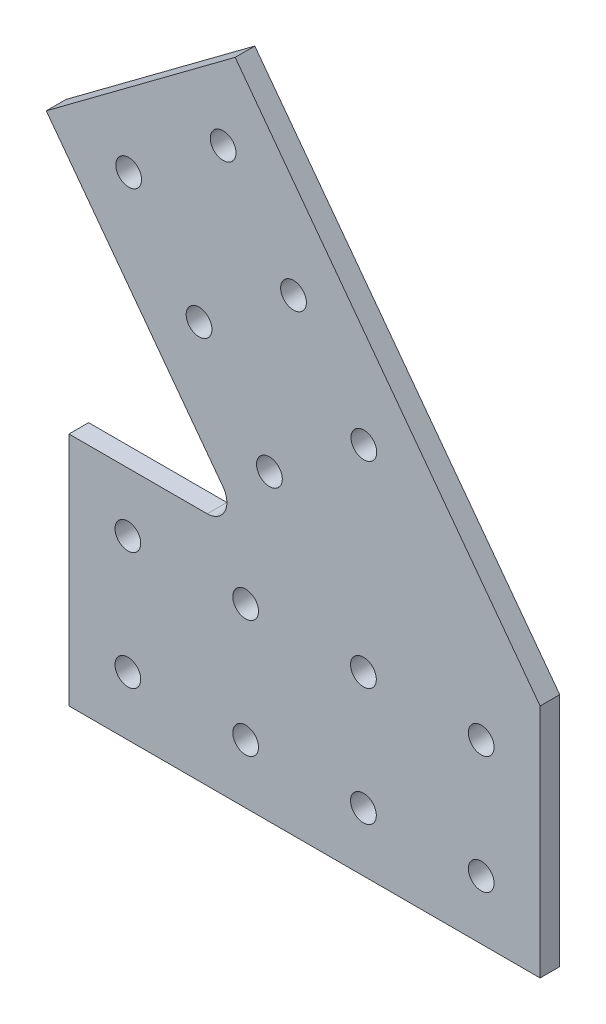
SolidWorks part; units mm, degrees
material "6061-T6 (SS)"
ref_plane "Front" through (0, 0, 0) normal (0, 0, 1) x (1, 0, 0)
ref_plane "Top" through (0, 0, 0) normal (0, 1, 0) x (1, 0, 0)
ref_plane "Right" through (0, 0, 0) normal (1, 0, 0) x (0, 0, -1)
sketch "Sketch2" plane through (0, 0, 0) normal (0, 0, 1) x (1, 0, 0)
  line L0 (0, 0) -> (152.4, 0)
  line L1 (152.4, 0) -> (152.4, 76.2)
  line L2 (152.4, 76.2) -> (53.7552, 208.5904)
  line L3 (53.7552, 208.5904) -> (-7.3481, 163.062)
  line L4 (-7.3481, 163.062) -> (57.3733, 76.2)
  line L5 (57.3733, 76.2) -> (0, 76.2)
  line L6 (0, 76.2) -> (0, 0)
  dimension "D1" = 152.4
  dimension "D2" = 76.2
  dimension "D3" = 76.2
  dimension "D4" = 76.2
  dimension "D5" = 53.31
  dimension "D6" = 165.1
extrude "Boss-Extrude1" add sketch "Sketch2" along normal blind 6.35
hole_wizard "21/64 (0.32813) Diameter Hole1" positions "Sketch3" profile "Sketch4" hole size "21/64" standard "ANSI Inch" end condition through all
sketch "Sketch3" plane through (0, 0, 6.35) normal (0, 0, 1) x (1, 0, 0)
  line L0 (152.4, 0) -> (152.4, 76.2) construction
  line L1 (0, 0) -> (152.4, 0) construction
  point P0 (133.35, 19.05)
  dimension "D1" = 19.05
  dimension "D2" = 19.05
sketch "Sketch4" plane through (133.35, 19.05, 6.35) normal (1, 0, 0) x (0, -1, 0)
  line L0 (0, 0) -> (0, 6.35)
  line L1 (0, 6.35) -> (4.1673, 6.35)
  line L2 (4.1673, 6.35) -> (4.1673, 0)
  line L5 (4.1673, 0) -> (0, 0)
  line L11 (0, -6.35) -> (0, 107.95) construction
  dimension "Thru Hole Dia." = 8.3345
  dimension "Thru Hole Depth" = 6.35
pattern_linear "LPattern1" count 4 spacing 38.1 along (-1, 0, 0) count 2 spacing 38.1 along (0, 1, 0) of "21/64 (0.32813) Diameter Hole1"
hole_wizard "21/64 (0.32813) Diameter Hole2" positions "Sketch5" profile "Sketch6" hole size "21/64" standard "ANSI Inch" end condition through all
sketch "Sketch5" plane through (0, 0, 6.35) normal (0, 0, 1) x (1, 0, 0)
  line L0 (152.4, 76.2) -> (53.7552, 208.5904) construction
  line L1 (53.7552, 208.5904) -> (-7.3481, 163.062) construction
  point P0 (49.8615, 181.9325)
  dimension "D1" = 19.05
  dimension "D2" = 19.05
sketch "Sketch6" plane through (49.8615, 181.9325, 6.35) normal (1, 0, 0) x (0, -1, 0)
  line L0 (0, 0) -> (0, 6.35)
  line L1 (0, 6.35) -> (4.1673, 6.35)
  line L2 (4.1673, 6.35) -> (4.1673, 0)
  line L5 (4.1673, 0) -> (0, 0)
  line L11 (0, -6.35) -> (0, 107.95) construction
  dimension "Thru Hole Dia." = 8.3345
  dimension "Thru Hole Depth" = 6.35
pattern_linear "LPattern2" count 3 spacing 38.1 along (0.5975, -0.8019, 0) count 2 spacing 38.1 along (-0.8019, -0.5975, 0) of "21/64 (0.32813) Diameter Hole2"
fillet "Fillet1" radius 6.35 1 edges at (57.3733, 76.2, 3.175)
